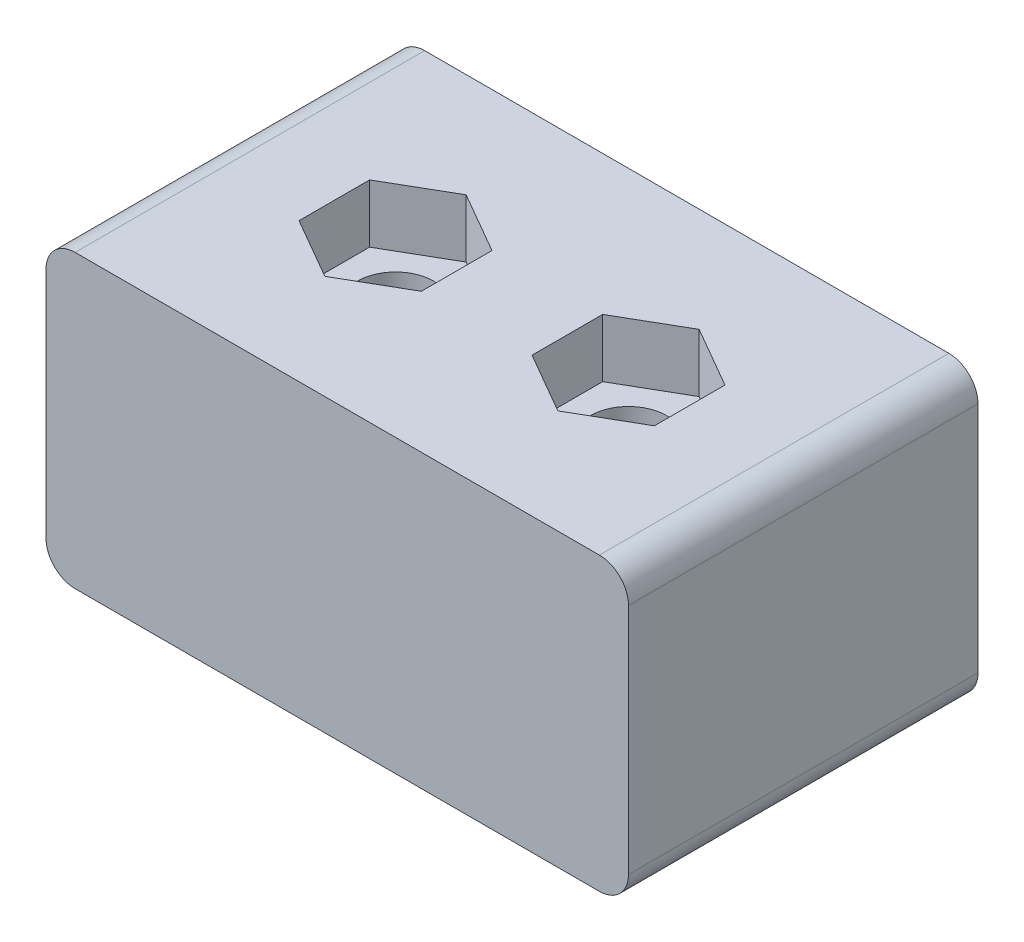
SolidWorks part; units mm, degrees
ref_plane "Front Plane" through (0, 0, 0) normal (0, 0, 1) x (1, 0, 0)
ref_plane "Top Plane" through (0, 0, 0) normal (0, 1, 0) x (1, 0, 0)
ref_plane "Right Plane" through (0, 0, 0) normal (1, 0, 0) x (0, 0, -1)
sketch "Sketch1" plane through (0, 0, 0) normal (0, 0, 1) x (1, 0, 0)
  line L0 (-9, 0) -> (9, 0)
  line L1 (10, 1) -> (10, 9)
  line L2 (9, 10) -> (-9, 10)
  line L3 (-10, 9) -> (-10, 1)
  arc A0 (9, 0) -> (10, 1) centre (9, 1) ccw
  arc A1 (10, 9) -> (9, 10) centre (9, 9) ccw
  arc A2 (-9, 10) -> (-10, 9) centre (-9, 9) ccw
  arc A3 (-10, 1) -> (-9, 0) centre (-9, 1) ccw
extrude "Boss-Extrude1" add sketch "Sketch1" along normal mid plane 12
sketch "Sketch2" plane through (0, 0, 0) normal (0, 1, 0) x (1, 0, 0)
  circle A0 centre (4, 0) radius 1.3
  circle A1 centre (-4, 0) radius 1.3
extrude "Cut-Extrude1" cut sketch "Sketch2" along normal blind 10
ref_plane "Plane1" through (0, 10, 0) normal (0, 1, 0) x (1, 0, 0)
sketch "Sketch3" plane through (0, 10, 0) normal (0, 1, 0) x (1, 0, 0)
  line L0 (6.1, -1.2124) -> (4, -2.4249)
  line L1 (4, -2.4249) -> (1.9, -1.2124)
  line L2 (1.9, -1.2124) -> (1.9, 1.2124)
  line L3 (1.9, 1.2124) -> (4, 2.4249)
  line L4 (4, 2.4249) -> (6.1, 1.2124)
  line L5 (6.1, 1.2124) -> (6.1, -1.2124)
  line L6 (-1.9, -1.2124) -> (-4, -2.4249)
  line L7 (-4, -2.4249) -> (-6.1, -1.2124)
  line L8 (-6.1, -1.2124) -> (-6.1, 1.2124)
  line L9 (-6.1, 1.2124) -> (-4, 2.4249)
  line L10 (-4, 2.4249) -> (-1.9, 1.2124)
  line L11 (-1.9, 1.2124) -> (-1.9, -1.2124)
extrude "Cut-Extrude2" cut sketch "Sketch3" against normal blind 2
